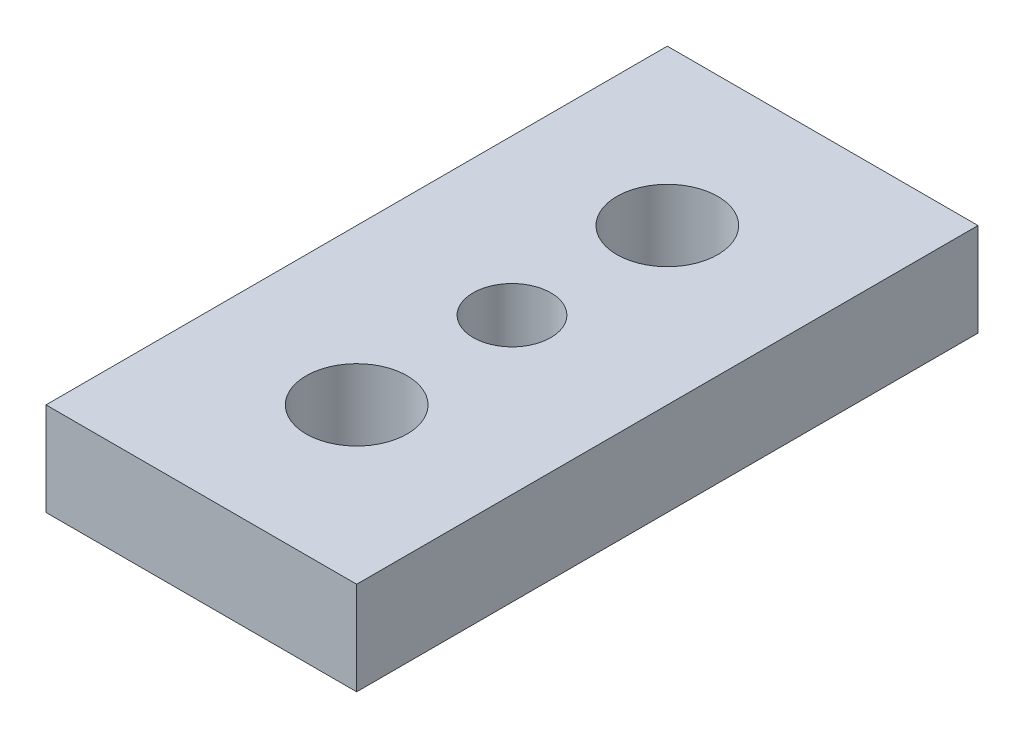
SolidWorks part; units mm, degrees
ref_plane "前视基准面" through (0, 0, 0) normal (0, 0, 1) x (1, 0, 0)
ref_plane "上视基准面" through (0, 0, 0) normal (0, 1, 0) x (1, 0, 0)
ref_plane "右视基准面" through (0, 0, 0) normal (1, 0, 0) x (0, 0, -1)
sketch "草图1" plane through (0, 0, 0) normal (0, 1, 0) x (1, 0, 0)
  line B0 (0, 40) -> (0, 0)
  line B1 (0, 0) -> (20, 0)
  line B2 (0, 40) -> (20, 40)
  line B3 (20, 40) -> (20, 0)
  circle B4 centre (10, 30) radius 3.25
  circle B5 centre (10, 10) radius 3.25
sketch_block_instance "A$C3CEF4A16-1"
sketch_block "A$C3CEF4A16"
extrude "凸台-拉伸1" add sketch "草图1" along normal blind 6
sketch "草图3" plane through (0, 6, 0) normal (0, 1, 0) x (1, 0, 0)
  point P0 (10, 20)
hole_wizard "M6 螺纹孔1" positions "3D草图1" profile "草图4" tap size "M6" standard "Iso" end condition through all
sketch3d "3D草图1"
  point P0 (10, 6, -20)
sketch "草图4" plane through (10, 6, -20) normal (1, 0, 0) x (0, 0, 1)
  line L0 (0, 0) -> (0, 6)
  line L1 (0, 6) -> (2.5, 6)
  line L2 (2.5, 6) -> (2.5, 0)
  line L5 (2.5, 0) -> (0, 0)
  line L11 (0, -6.35) -> (0, 107.95) construction
  dimension "通孔螺纹孔钻头直径" = 5
  dimension "通孔螺纹孔钻头深度" = 6
cosmetic thread "孔螺蚊线1"
